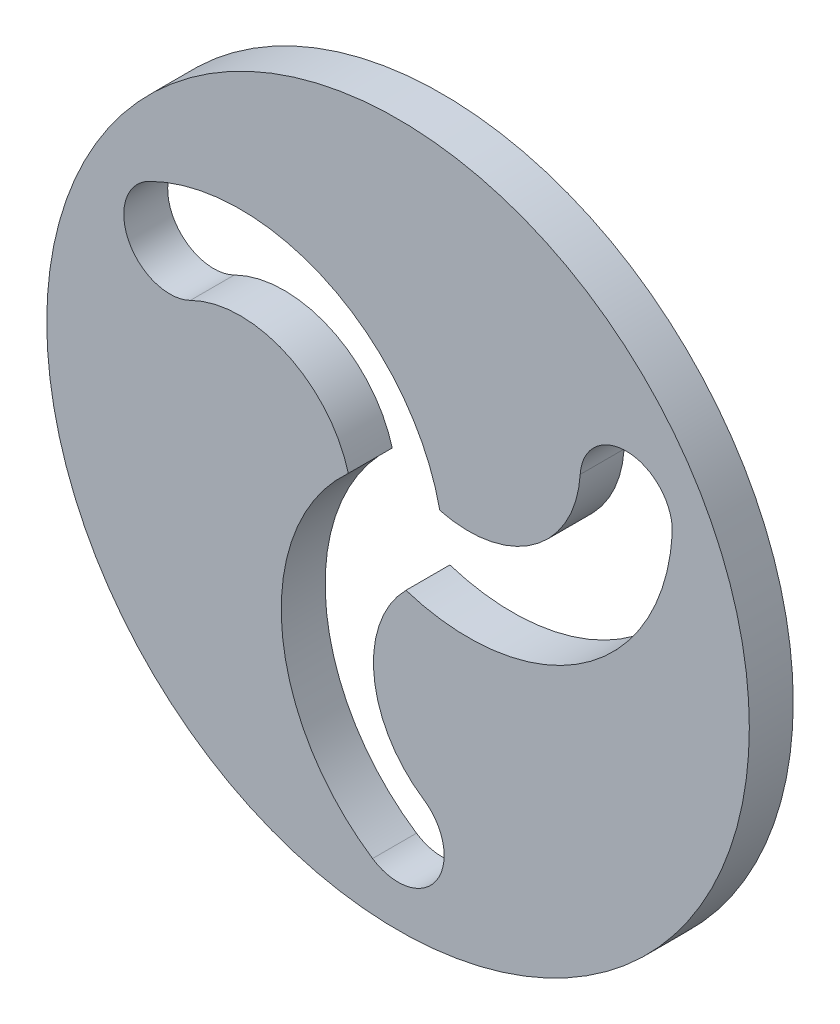
SolidWorks part; units mm, degrees
ref_plane "Alzado" through (0, 0, 0) normal (0, 0, 1) x (1, 0, 0)
ref_plane "Planta" through (0, 0, 0) normal (0, 1, 0) x (1, 0, 0)
ref_plane "Vista lateral" through (0, 0, 0) normal (1, 0, 0) x (0, 0, -1)
sketch "Croquis1" plane through (0, 0, 0) normal (0, 0, 1) x (1, 0, 0)
  circle A0 centre (0, 0) radius 40
  dimension "D1" = 80
extrude "Disco" add sketch "Croquis1" along normal blind 5
sketch "Croquis6" plane through (0, 0, 5) normal (0, 0, 1) x (1, 0, 0)
  line L6 (0, 0) -> (0, -30) construction
  circle A7 centre (0, -30) radius 5.25
  circle A8 centre (0, 0) radius 5.25
  arc A9 (0, -30) -> (0, 0) centre (9.9499, -15) cw
  arc A10 (2.902, -25.625) -> (2.902, -4.375) centre (9.9499, -15) cw
  arc A11 (-2.902, -34.375) -> (-2.902, 4.375) centre (9.9499, -15) cw
  circle A12 centre (0, 0) radius 5.25
  arc A13 (-28.3186, 19.7007) -> (5.2399, 0.3257) centre (-17.9653, -1.1168) cw
  arc A14 (-23.6429, 10.2993) -> (-5.2399, -0.3257) centre (-17.9653, -1.1168) cw
  circle A15 centre (-25.9808, 15) radius 5.25
  circle A16 centre (0, 0) radius 5.25
  arc A17 (31.2206, 14.6743) -> (-2.3378, -4.7007) centre (8.0154, 16.1168) cw
  arc A18 (20.7409, 15.3257) -> (2.3378, 4.7007) centre (8.0154, 16.1168) cw
  circle A19 centre (25.9808, 15) radius 5.25
  point P22 (0, 0)
  point P33 (0, 0)
  dimension "D1" = 30
  dimension "D3" = 10.5
  dimension "D5" = 5.25
  dimension "D2" = 10.5
  dimension "D6" = 18
  dimension "D4" = 5.25
  dimension "D7" = 3
extrude "Cortar-Extruir1" cut sketch "Croquis6" against normal blind 10 contours A18 A13 A15 A14 A11 A16 | A19 A18 A13 A8 A10 A17 | A14 A11 A7 A9 A12 | L6 A17 A8 A9 A7 A10 | A11 A14 A8 | A13 A18 A12 | A8 L6 A17 A10 | L6 A16 A17 | A9 L6 A8 A12 A16 | L6 A9 A8 A16 | A10 L6 A7 | A17 L6 A10
sketch "Croquis7" plane through (0, 0, 0) normal (0, 0, -1) x (-1, 0, 0)
  line L0 (0, 0) -> (0, 30) construction
  circle A0 centre (0, 30) radius 5
  circle A1 centre (25.9808, -15) radius 5
  circle A2 centre (-25.9808, -15) radius 5
  point P10 (0, 0)
  dimension "D2" = 10
  dimension "D1" = 30
  dimension "D3" = 3
extrude "Saliente-Extruir2" add sketch "Croquis7" along normal blind 2
